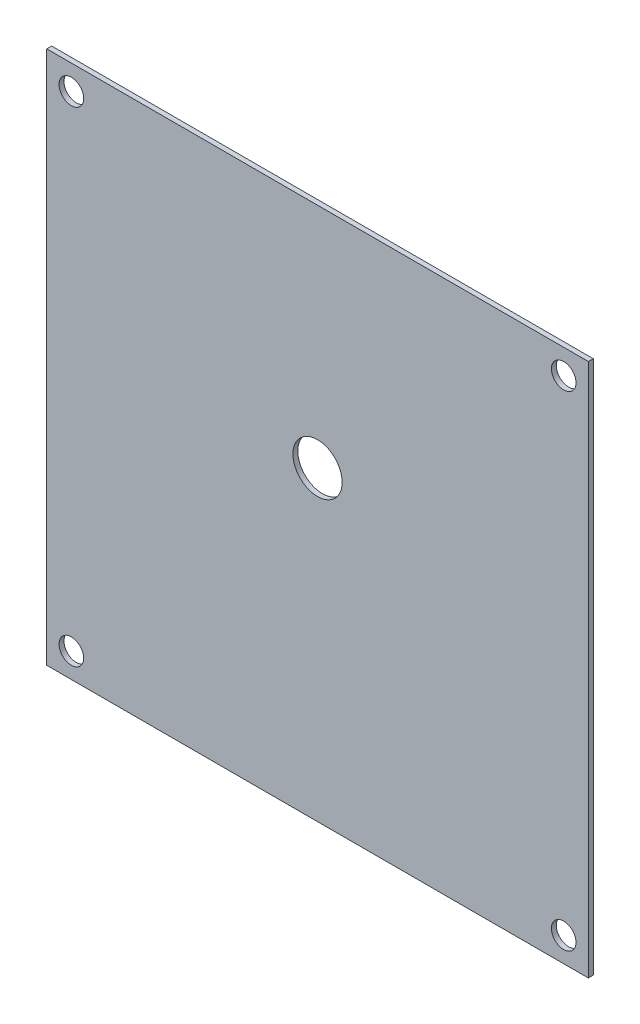
SolidWorks part; units mm, degrees
ref_plane "Front Plane" through (0, 0, 0) normal (0, 0, 1) x (1, 0, 0)
ref_plane "Top Plane" through (0, 0, 0) normal (0, 1, 0) x (1, 0, 0)
ref_plane "Right Plane" through (0, 0, 0) normal (1, 0, 0) x (0, 0, -1)
sketch "Sketch1" plane through (0, 0, 0) normal (0, 0, 1) x (1, 0, 0)
  line L0 (55, 0) -> (-55, 0) construction
  line L1 (-139.7, 137.7156) -> (139.7, 137.7156)
  line L2 (-139.7, 137.7156) -> (-139.7, -137.7156)
  line L3 (-139.7, -137.7156) -> (139.7, -137.7156)
  line L4 (139.7, 137.7156) -> (139.7, -137.7156)
  line L5 (-139.7, 137.7156) -> (139.7, -137.7156) construction
  line L6 (-139.7, -137.7156) -> (139.7, 137.7156) construction
  line L7 (0, -55) -> (0, 55) construction
  line L8 (-139.7, 20.2406) -> (0, 20.2406) construction
  line L10 (0, 20.2406) -> (0, -137.7156) construction
  line L11 (0, 20.2406) -> (0, 137.7156) construction
  circle A0 centre (-127, 125.0156) radius 6.35
  circle A1 centre (-127, -125.0156) radius 6.35
  circle A2 centre (127, -125.0156) radius 6.35
  circle A3 centre (127, 125.0156) radius 6.35
  circle A4 centre (0, 20.2406) radius 12.7
  point P0 (0, 0)
  dimension "D1" = 12.7
  dimension "D2" = 12.7
  dimension "D3" = 279.4
  dimension "D4" = 275.4313
extrude "Boss-Extrude1" add sketch "Sketch1" along normal blind 2.54
